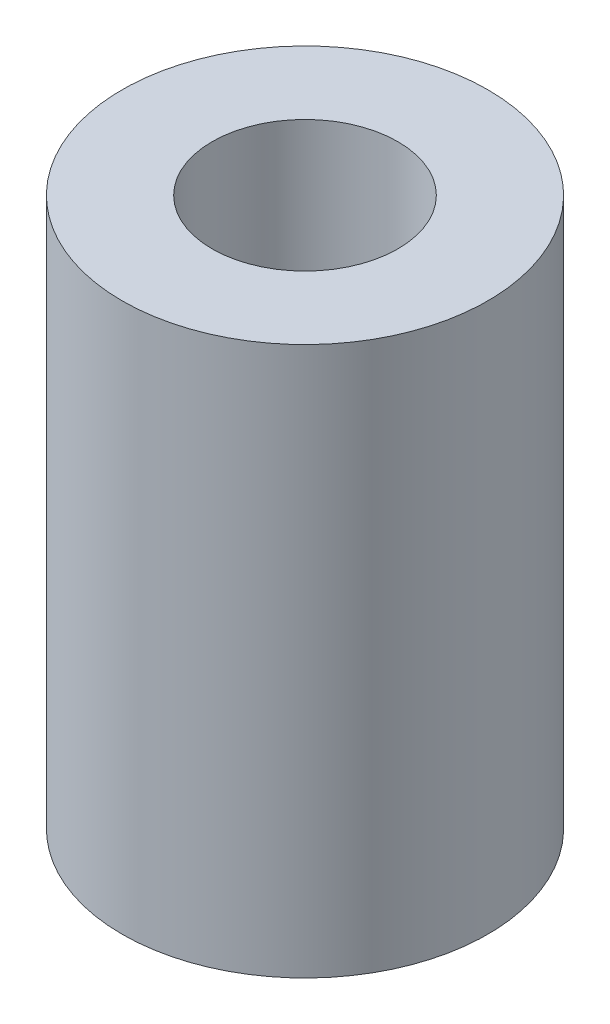
SolidWorks part; units mm, degrees
ref_plane "前视基准面" through (0, 0, 0) normal (0, 0, 1) x (1, 0, 0)
ref_plane "上视基准面" through (0, 0, 0) normal (0, 1, 0) x (1, 0, 0)
ref_plane "右视基准面" through (0, 0, 0) normal (1, 0, 0) x (0, 0, -1)
sketch "草图1" plane through (0, 0, 0) normal (0, 1, 0) x (1, 0, 0)
  circle A0 centre (0, 0) radius 2.54
  circle A1 centre (0, 0) radius 5
extrude "凸台-拉伸1" add sketch "草图1" along normal blind 15
